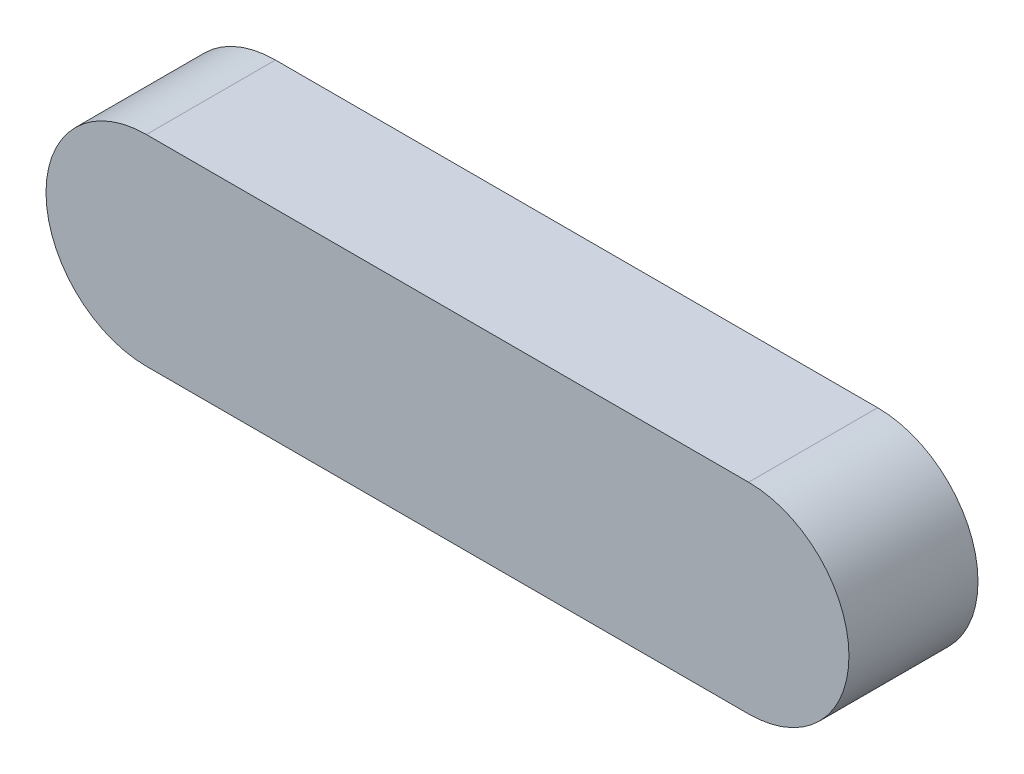
SolidWorks part; units mm, degrees
material "ASTM A36 Steel"
ref_plane "Front Plane" through (0, 0, 0) normal (0, 0, 1) x (1, 0, 0)
ref_plane "Top Plane" through (0, 0, 0) normal (0, 1, 0) x (1, 0, 0)
ref_plane "Right Plane" through (0, 0, 0) normal (1, 0, 0) x (0, 0, -1)
sketch "Sketch1" plane through (0, 0, 0) normal (0, 0, 1) x (1, 0, 0)
  line L0 (-21, 0) -> (21, 0) construction
  line L1 (-21, 7) -> (21, 7)
  line L2 (-21, -7) -> (21, -7)
  arc A0 (-21, 7) -> (-21, -7) centre (-21, 0) ccw
  arc A1 (21, -7) -> (21, 7) centre (21, 0) ccw
  point P2 (0, 0)
  dimension "D2" = 7
  dimension "D1" = 42
extrude "Boss-Extrude1" add sketch "Sketch1" along normal blind 9 contours L1 A1 L2 A0
